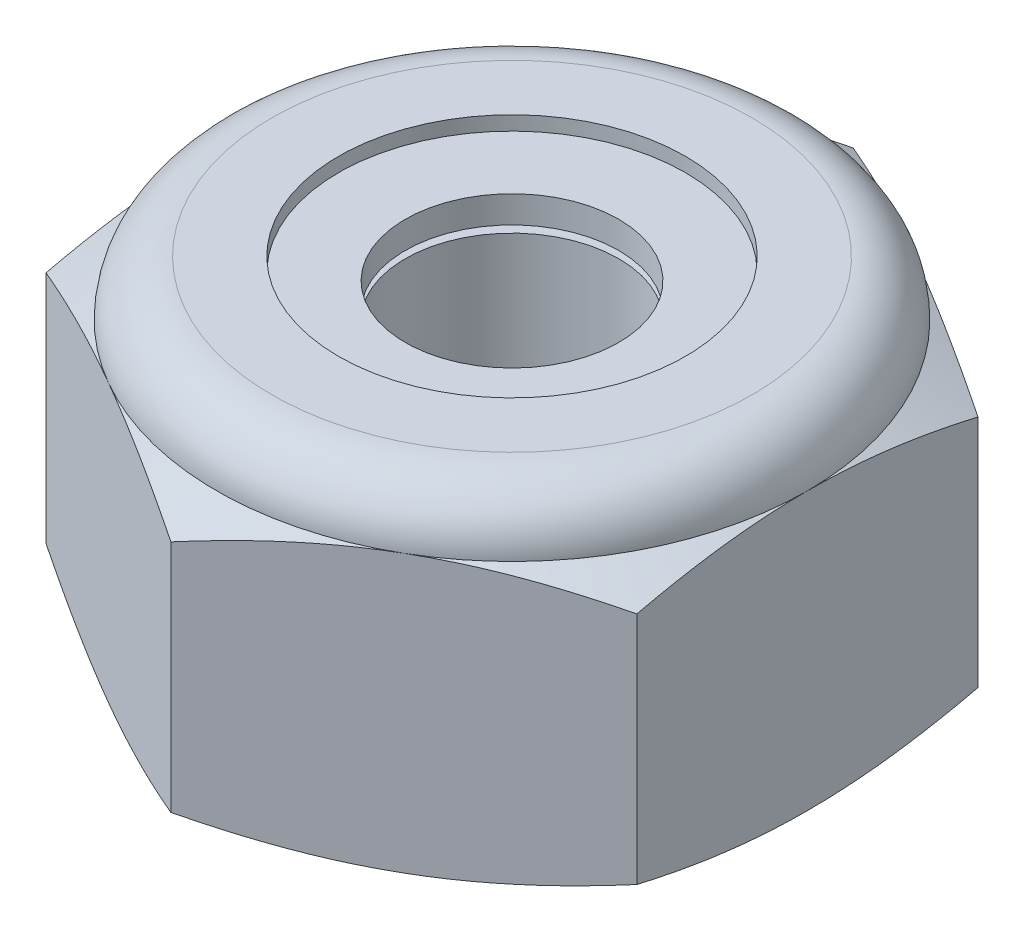
SolidWorks part; units mm, degrees
material "Alloy Steel"
ref_plane "Front" through (0, 0, 0) normal (0, 0, 1) x (1, 0, 0)
ref_plane "Top" through (0, 0, 0) normal (0, 1, 0) x (1, 0, 0)
ref_plane "Right" through (0, 0, 0) normal (1, 0, 0) x (0, 0, -1)
sketch "Sketch1" plane through (0, 0, 0) normal (0, 1, 0) x (1, 0, 0)
  line L1 (0, 3.6662) -> (-3.175, 1.8331)
  line L2 (-3.175, 1.8331) -> (-3.175, -1.8331)
  line L3 (-3.175, -1.8331) -> (0, -3.6662)
  line L4 (0, -3.6662) -> (3.175, -1.8331)
  line L5 (3.175, -1.8331) -> (3.175, 1.8331)
  line L6 (3.175, 1.8331) -> (0, 3.6662)
  circle A0 centre (0, 0) radius 3.175 construction
  dimension "Hex Flats" = 6.35
extrude "Extrude1" add sketch "Sketch1" along normal blind 3.5719
sketch "Sketch4" plane through (0, 0, 0) normal (1, 0, 0) x (0, 0, -1)
  line L0 (0, 3.5719) -> (1.4224, 3.5719)
  line L1 (1.4224, 3.5719) -> (1.1475, 3.4437)
  line L2 (1.1475, 3.4437) -> (1.1475, 0.1282)
  line L3 (1.1475, 0.1282) -> (1.4224, 0)
  line L4 (1.4224, 0) -> (0, 0)
  line L5 (0, 0) -> (0, 3.5719)
  line L10 (0, 3.5719) -> (0, 3.8752) construction
  line L11 (-1.8331, 0) -> (1.8331, 0) construction
  line L12 (-1.8331, 3.5719) -> (1.8331, 3.5719) construction
  dimension "D2" = 1.1475
  dimension "D3" = 0.1282
  dimension "D4" = 0.1282
revolve "Cut-Revolve2" cut sketch "Sketch4" angle 360 about L10
sketch "Sketch5" plane through (0, 0, 0) normal (1, 0, 0) x (0, 0, -1)
  line L0 (0, 0) -> (3.175, 0)
  line L1 (3.175, 0) -> (3.6662, 0.229)
  line L2 (3.6662, 0.229) -> (3.6662, 2.7475)
  line L3 (3.6662, 2.7475) -> (3.175, 2.9766)
  line L4 (2.5797, 3.5719) -> (2.5797, 4.8419)
  line L5 (2.5797, 4.8419) -> (4.9362, 4.8419)
  line L6 (4.9362, 4.8419) -> (4.9362, -1.27)
  line L7 (4.9362, -1.27) -> (0, -1.27)
  line L8 (0, -1.27) -> (0, 0)
  line L9 (3.175, 2.9766) -> (3.175, 0) construction
  line L11 (-1.8331, 0) -> (1.8331, 0) construction
  line L13 (3.6662, 1.4883) -> (4.9362, 1.4883) construction
  line L14 (3.6662, 3.5719) -> (3.6662, 0) construction
  line L15 (0, 0) -> (0, 4.8419) construction
  line L20 (0, 4.8419) -> (2.5797, 4.8419) construction
  arc A0 (3.175, 2.9766) -> (2.5797, 3.5719) centre (2.5797, 2.9766) ccw
  dimension "D1" = 25
  dimension "D2" = 1.27
  dimension "D3" = 3.5719
revolve "Cut-Revolve3" cut sketch "Sketch5" angle 360 about L15
sketch "Sketch6" plane through (0, 0, 0) normal (1, 0, 0) x (0, 0, -1)
  line L0 (1.1475, 2.9766) -> (3.0226, 2.9766)
  line L1 (2.5797, 3.4195) -> (1.8636, 3.4195)
  line L2 (1.1475, 4.8419) -> (1.1475, 2.9766)
  line L3 (1.8636, 4.8419) -> (1.1475, 4.8419)
  line L4 (0, 4.8419) -> (2.5797, 4.8419) construction
  line L6 (0, 0) -> (0, 4.8419) construction
  line L7 (1.8636, 3.4195) -> (1.8636, 4.8419)
  line L8 (2.5797, 3.5719) -> (2.5797, 3.4195) construction
  line L9 (1.8636, 3.4195) -> (1.1475, 3.4195) construction
  line L10 (1.1475, 3.4195) -> (1.1475, 3.4437) construction
  line L13 (1.1475, 0.1282) -> (1.1475, 3.4437) construction
  arc A0 (3.0226, 2.9766) -> (2.5797, 3.4195) centre (2.5797, 2.9766) ccw
  arc A1 (3.175, 2.9766) -> (2.5797, 3.5719) centre (2.5797, 2.9766) ccw construction
  dimension "D1" = 0.1524
revolve "Cut-Revolve4" cut sketch "Sketch6" angle 360 about L6
sketch "Sketch7" plane through (0, 0, 0) normal (1, 0, 0) x (0, 0, -1)
  line L0 (1.1475, 3.0528) -> (2.9384, 3.0528)
  line L1 (2.5797, 3.3433) -> (1.1475, 3.3433)
  line L2 (1.1475, 3.3433) -> (1.1475, 3.0528)
  line L3 (1.1475, 3.0528) -> (0, 3.0528) construction
  line L4 (0, 3.0528) -> (0, 3.3433) construction
  line L5 (0, 3.3433) -> (1.1475, 3.3433) construction
  line L6 (1.1475, 3.0528) -> (1.1475, 2.9766) construction
  line L7 (1.1475, 2.9766) -> (3.0226, 2.9766) construction
  line L8 (2.5797, 3.3433) -> (2.5797, 3.4195) construction
  line L9 (1.1475, 0.1282) -> (1.1475, 2.9766) construction
  arc A0 (2.9384, 3.0528) -> (2.5797, 3.3433) centre (2.5797, 2.9766) ccw
  arc A2 (3.0226, 2.9766) -> (2.5797, 3.4195) centre (2.5797, 2.9766) ccw construction
  dimension "D1" = 0.0762
revolve "Revolve2" add sketch "Sketch7" angle 360 about L4
